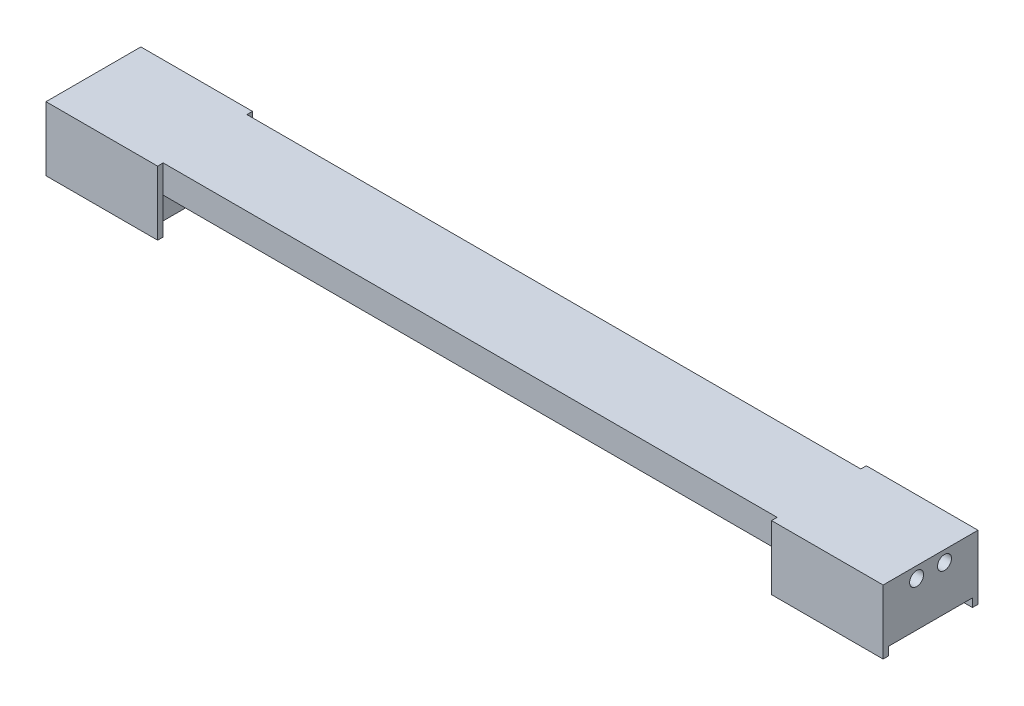
SolidWorks part; units mm, degrees
ref_plane "Ebene vorne" through (0, 0, 0) normal (0, 0, 1) x (1, 0, 0)
ref_plane "Ebene oben" through (0, 0, 0) normal (0, 1, 0) x (1, 0, 0)
ref_plane "Ebene rechts" through (0, 0, 0) normal (1, 0, 0) x (0, 0, -1)
sketch "Skizze1" plane through (0, 0, 0) normal (0, 0, 1) x (1, 0, 0)
  line L0 (0, 0) -> (31694.6402, 0) construction
  line L1 (0, 0) -> (0, 31694.6402) construction
  line L2 (-74, 0) -> (-74, -10)
  line L3 (-74, 0) -> (74, 0)
  line L5 (-56, -5) -> (56, -5)
  line L6 (-56, -10) -> (-74, -10)
  line L7 (-56, -5) -> (-56, -10)
  line L8 (56, -5) -> (56, -10)
  line L9 (56, -10) -> (74, -10)
  line L10 (74, 0) -> (74, -10)
  dimension "D1" = 56
  dimension "D2" = 5
  dimension "D3" = 5
  dimension "D4" = 18
extrude "Aufsatz-Linear austragen1" add sketch "Skizze1" along normal blind 15
sketch "Skizze5" plane through (0, -10, 0) normal (0, -1, 0) x (1, 0, 0)
  line L4 (56, 15) -> (56, 0) construction
  line L7 (56, 0) -> (55, 0)
  line L8 (55, -1) -> (75, -1)
  line L9 (75, -1) -> (75, 16)
  line L10 (75, 16) -> (55, 16)
  line L11 (55, 16) -> (55, -1)
  line L12 (56, -1) -> (75, -1)
  line L13 (75, -1) -> (75, 16)
  line L14 (75, 16) -> (56, 16)
  line L16 (56, 0) -> (74, 0)
  line L17 (74, 0) -> (74, 15)
  line L18 (74, 15) -> (56, 15)
  line L19 (56, 15) -> (56, 0)
  line L20 (56, 0) -> (74, 0)
  line L21 (74, 0) -> (74, 15)
  line L22 (74, 15) -> (56, 15)
  line L23 (56, -1) -> (55, -1)
  line L24 (55, 0) -> (55, -1)
  line L25 (56, 15) -> (55, 15)
  line L27 (56, 16) -> (55, 16)
  line L28 (55, 15) -> (55, 16)
  dimension "D3" = 1
  dimension "D1" = 1
  dimension "D2" = 0
extrude "Aufsatz-Linear austragen4" add sketch "Skizze5" along normal blind 1.5 and the other way up to surface other way up to face at (0, 0, 7.5)
mirror "Spiegeln1" about plane through (0, 0, 0) normal (1, 0, 0) of "Aufsatz-Linear austragen4"
sketch "Skizze6" plane through (-75, 0, 0) normal (-1, 0, 0) x (0, 0, 1)
  line L0 (7.5, 0) -> (7.5, 50000) construction
  line L1 (16, 0) -> (-1, 0) construction
  line L2 (7.5, -2) -> (-49992.5, -2) construction
  line L7 (0, -10) -> (0, -11.5)
  line L8 (15, -10) -> (0, -10)
  line L9 (15, -11.5) -> (15, -10)
  line L10 (0, -11.5) -> (15, -11.5)
  line L11 (0, -10) -> (0, -11.5)
  line L12 (15, -10) -> (0, -10)
  line L13 (15, -11.5) -> (15, -10)
  line L14 (0, -11.5) -> (15, -11.5)
  circle A0 centre (10, -2) radius 1.25
  circle A1 centre (5, -2) radius 1.25
  point P4 (7.5, 0)
  dimension "D1" = 2.5
  dimension "D2" = 2
  dimension "D3" = 5
  dimension "D4" = 0
extrude "Schnitt-Linear austragen1" cut sketch "Skizze6" against normal through all
ref_plane "Ebene1" through (0, 0, 7.5) normal (0, 0, 1) x (1, 0, 0)
